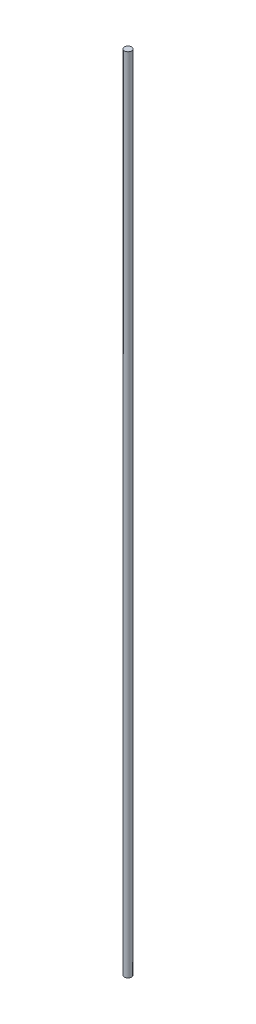
SolidWorks part; units mm, degrees
material "Polyethylene Cross-Linked"
ref_plane "Alzado" through (0, 0, 0) normal (0, 0, 1) x (1, 0, 0)
ref_plane "Planta" through (0, 0, 0) normal (0, 1, 0) x (1, 0, 0)
ref_plane "Vista lateral" through (0, 0, 0) normal (1, 0, 0) x (0, 0, -1)
sketch "Sketch1" plane through (0, 0, 0) normal (0, 0, 1) x (1, 0, 0)
  line L0 (0, -36) -> (0.75, -36)
  line L1 (0.75, -36) -> (0.75, -206)
  line L2 (0.75, -206) -> (0, -206)
  line L3 (0, -206) -> (0, -36)
  line L4 (0, -210) -> (0, -32) construction
revolve "Cuerdas_UHMWPE" add sketch "Sketch1" angle 360 about L4
